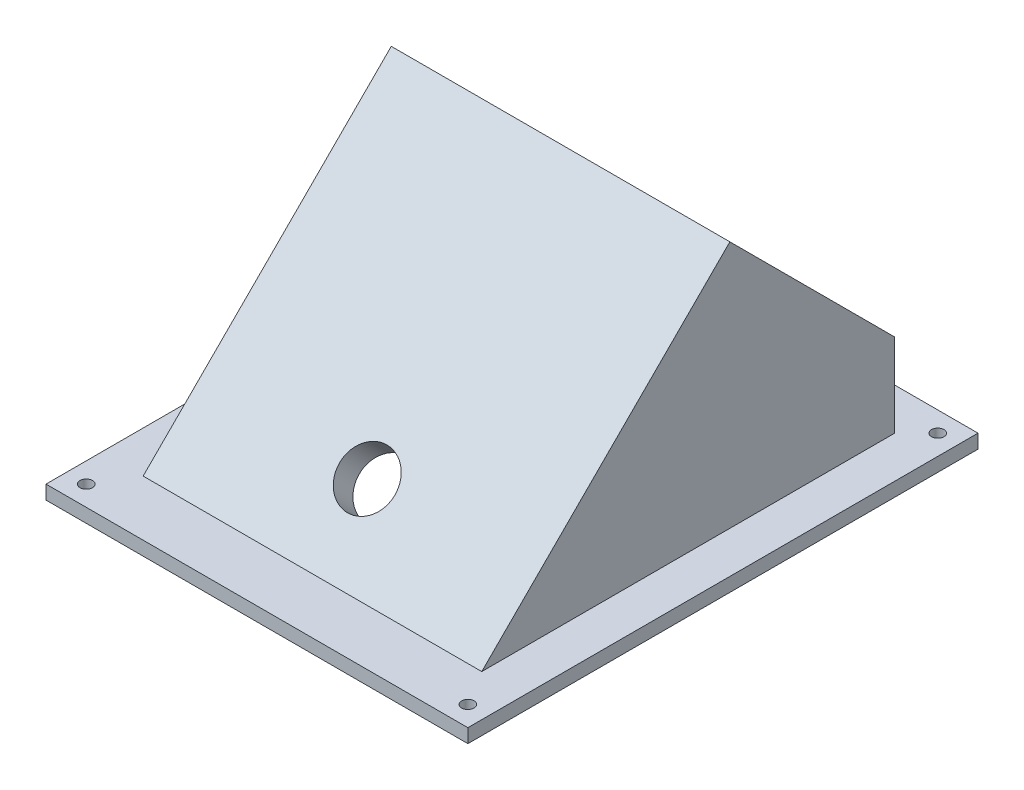
SolidWorks part; units mm, degrees
ref_plane "Piano frontale" through (0, 0, 0) normal (0, 0, 1) x (1, 0, 0)
ref_plane "Piano superiore" through (0, 0, 0) normal (0, 1, 0) x (1, 0, 0)
ref_plane "Piano destro" through (0, 0, 0) normal (1, 0, 0) x (0, 0, -1)
sketch "Schizzo1" plane through (0, 0, 0) normal (1, 0, 0) x (0, 0, -1)
  line L0 (0, 0) -> (0, 35)
  line L1 (0, 35) -> (-59.397, 94.397)
  line L2 (-59.397, 94.397) -> (-153.7939, 0)
  line L3 (-153.7939, 0) -> (0, 0)
  line L4 (-87.6812, 66.1127) -> (-28.2843, 6.7157) construction
  line L5 (-28.2843, 6.7157) -> (0, 35) construction
  point P7 (0, 28.3441)
  point P8 (-188.5209, 0)
  point P9 (0, 54.6075)
  point P10 (-172.0501, 0)
  dimension "D1" = 84
  dimension "D2" = 40
  dimension "D3" = 35
  dimension "D4" = 45
extrude "Estrusione-Estrusione1" add sketch "Schizzo1" along normal blind 122
sketch "Schizzo2" plane through (0, 17.5, -17.5) normal (0, 0.7071, -0.7071) x (1, 0, 0)
  line L0 (0, -24.7487) -> (122, -108.7487) construction
  line L1 (25, -39.2487) -> (97, -39.2487)
  line L2 (25, -39.2487) -> (25, -94.2487)
  line L3 (25, -94.2487) -> (97, -94.2487)
  line L4 (97, -39.2487) -> (97, -94.2487)
  line L5 (122, -24.7487) -> (0, -108.7487) construction
  line L6 (25, -94.2487) -> (97, -39.2487) construction
  line L7 (97, -94.2487) -> (25, -39.2487) construction
  point P12 (61, -66.7487)
  point P13 (61, -66.7487)
  point P14 (0, 0)
  dimension "D1" = 55
  dimension "D2" = 72
extrude "Taglio-Estrusione1" cut sketch "Schizzo2" against normal blind 40
shell "Svuota1" thickness 10
sketch "Schizzo3" plane through (0, -10.7843, 10.7843) normal (0, 0.7071, -0.7071) x (1, 0, 0)
  line L0 (25, -39.2487) -> (97, -94.2487) construction
  line L1 (25, -94.2487) -> (97, -94.2487) construction
  line L2 (25, -94.2487) -> (97, -39.2487) construction
  circle A0 centre (61, -66.7487) radius 10
  point P11 (81.125, -94.2487)
  point P13 (0, 0)
  point P14 (61, -66.7487)
  dimension "D1" = 20
extrude "Taglio-Estrusione2" cut sketch "Schizzo3" against normal blind 40
sketch "Schizzo4" plane through (0, 69.8259, 69.8259) normal (0, -0.7071, -0.7071) x (1, 0, 0)
  line L0 (61, 98.7487) -> (61, 73.7487) construction
  line L1 (112, 98.7487) -> (10, 98.7487) construction
  circle A0 centre (61, 73.7487) radius 10
  dimension "D1" = 20
  dimension "D2" = 25
extrude "Taglio-Estrusione3" cut sketch "Schizzo4" against normal blind 40
sketch "Schizzo5" plane through (0, 0, 0) normal (0, -1, 0) x (1, 0, 0)
  line L0 (0, 153.7939) -> (0, 0) construction
  line L1 (137, -15) -> (-15, -15)
  line L2 (137, -15) -> (137, 168.7939)
  line L3 (137, 168.7939) -> (-15, 168.7939)
  line L4 (-15, -15) -> (-15, 168.7939)
  line L5 (122, 153.7939) -> (0, 153.7939) construction
  line L6 (122, 153.7939) -> (122, 0) construction
  line L7 (122, 0) -> (0, 0) construction
  line L9 (10, 139.6518) -> (122, 139.6518)
  line L10 (10, 139.6518) -> (10, 0)
  line L11 (10, 0) -> (122, 0)
  line L12 (122, 139.6518) -> (122, 0)
  dimension "D1" = 15
  dimension "D2" = 15
  dimension "D3" = 15
  dimension "D4" = 15
extrude "Estrusione-Estrusione2" add sketch "Schizzo5" against normal blind 5
sketch "Schizzo6" plane through (0, 5, 0) normal (0, 1, 0) x (1, 0, 0)
  line L1 (-7.75, 7.75) -> (129.75, 7.75) construction
  line L2 (-7.75, 7.75) -> (-7.75, -161.5439) construction
  line L3 (-7.75, -161.5439) -> (129.75, -161.5439) construction
  line L4 (129.75, 7.75) -> (129.75, -161.5439) construction
  line L6 (-15, -168.7939) -> (-15, 15) construction
  line L10 (-15, 15) -> (137, 15) construction
  line L12 (137, 15) -> (137, -168.7939) construction
  line L13 (137, -168.7939) -> (-15, -168.7939) construction
  point P0 (-7.75, -161.5439)
  point P2 (129.75, -161.5439)
  point P4 (129.75, 7.75)
  point P6 (-7.75, 7.75)
  dimension "D1" = 7.25
  dimension "D2" = 7.25
  dimension "D3" = 7.25
  dimension "D4" = 7.25
hole_wizard "Foro per Vite M4-1" positions "Schizzo6" profile "Schizzo7" hole size "M4" standard "DIN"
sketch "Schizzo7" plane through (-7.75, 5, 161.5439) normal (1, 0, 0) x (0, 0, 1)
  line L0 (0, 0) -> (0, 6.3519)
  line L1 (0, 6.3519) -> (2.25, 5)
  line L2 (2.25, 5) -> (2.25, 0)
  line L5 (2.25, 0) -> (0, 0)
  line L10 (0, 6.3519) -> (-2.25, 5) construction
  line L11 (0, -6.35) -> (0, 107.95) construction
  dimension "Hole Dia." = 4.5
  dimension "Hole Depth" = 5
  dimension "Drill Angle" = 118
